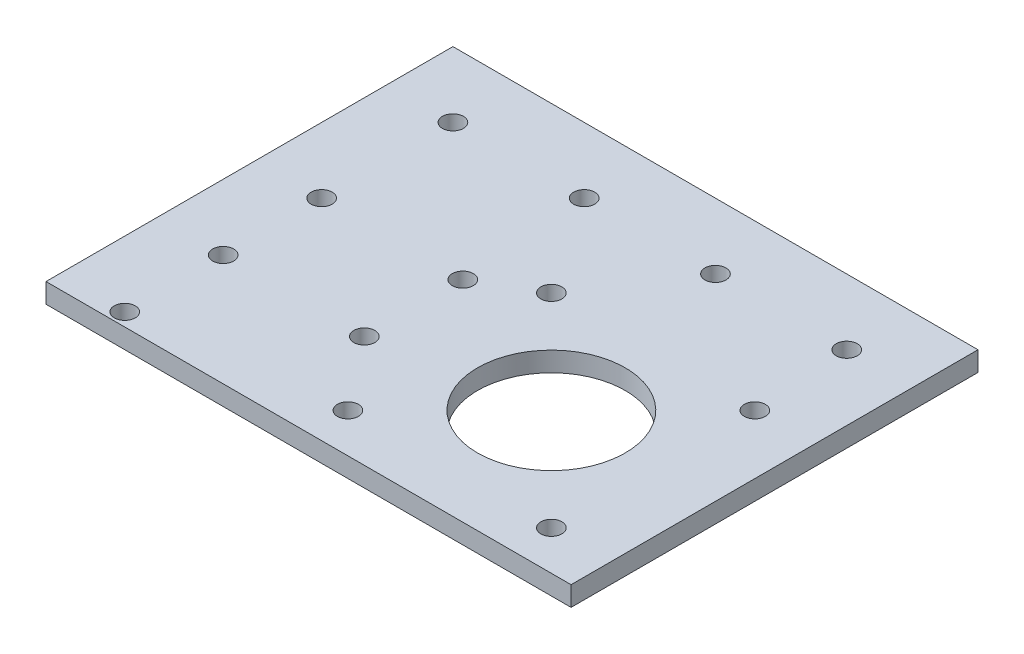
SolidWorks part; units mm, degrees
ref_plane "前视基准面" through (0, 0, 0) normal (0, 0, 1) x (1, 0, 0)
ref_plane "上视基准面" through (0, 0, 0) normal (0, 1, 0) x (1, 0, 0)
ref_plane "右视基准面" through (0, 0, 0) normal (1, 0, 0) x (0, 0, -1)
sketch "草图1" plane through (0, 0, 0) normal (0, 1, 0) x (1, 0, 0)
  line L0 (71, -25) -> (40, -56) construction
  line L1 (0, 0) -> (80, 0)
  line L2 (0, 0) -> (0, -62)
  line L3 (0, -62) -> (80, -62)
  line L4 (80, 0) -> (80, -62)
  line L5 (40, -25) -> (71, -56) construction
  circle A0 centre (10, -10) radius 1.6
  circle A1 centre (10, -30) radius 1.6
  circle A2 centre (10, -45) radius 1.6
  circle A3 centre (10, -60) radius 1.6
  circle A4 centre (30, -10) radius 1.6
  circle A7 centre (71, -25) radius 1.6
  circle A8 centre (40, -25) radius 1.6
  circle A9 centre (40, -56) radius 1.6
  circle A10 centre (71, -56) radius 1.6
  circle A11 centre (55.5, -40.5) radius 11.25
  circle A12 centre (50, -10) radius 1.6
  circle A13 centre (70, -10) radius 1.6
  circle A14 centre (31.5, -30) radius 1.6
  circle A15 centre (31.5, -45) radius 1.6
  point P28 (55.5, -40.5)
  dimension "D1" = 3.2
  dimension "D16" = 22.5
  dimension "D2" = 10
  dimension "D3" = 80
  dimension "D4" = 62
  dimension "D5" = 20
  dimension "D6" = 15
  dimension "D7" = 15
  dimension "D8" = 10
  dimension "D9" = 20
  dimension "D10" = 20
  dimension "D11" = 20
  dimension "D12" = 25
  dimension "D13" = 40
  dimension "D14" = 31
  dimension "D15" = 31
  dimension "D17" = 31.5
  dimension "D18" = 30
  dimension "D19" = 15
extrude "凸台-拉伸1" add sketch "草图1" along normal blind 3
